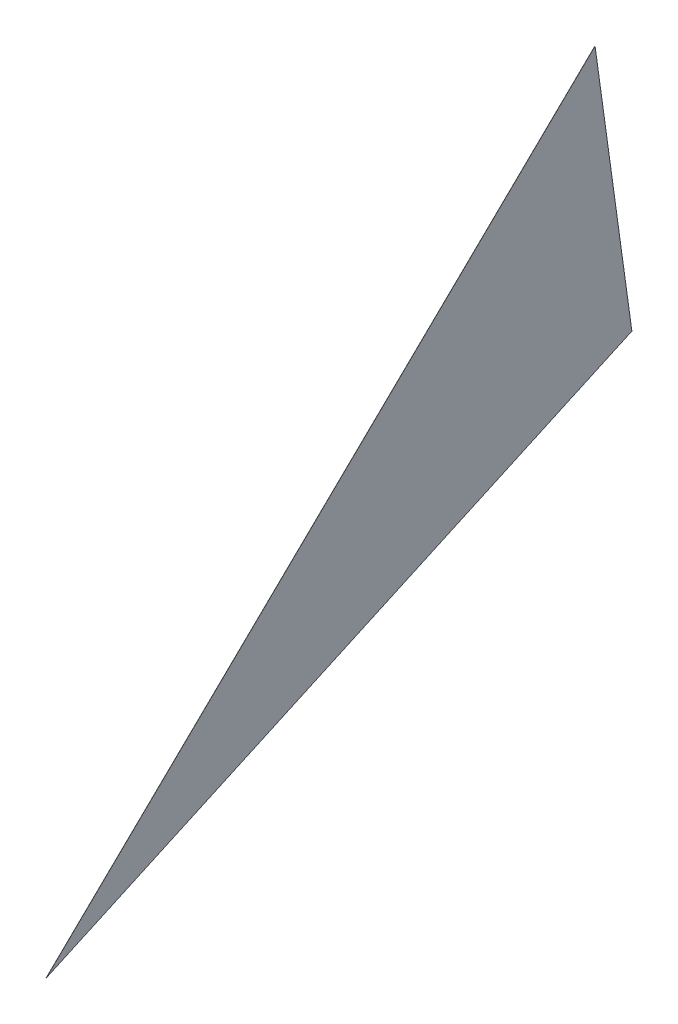
SolidWorks part; units mm, degrees
ref_plane "Front Plane" through (0, 0, 0) normal (0, 0, 1) x (1, 0, 0)
ref_plane "Top Plane" through (0, 0, 0) normal (0, 1, 0) x (1, 0, 0)
ref_plane "Right Plane" through (0, 0, 0) normal (1, 0, 0) x (0, 0, -1)
sketch "Sketch1" plane through (0, 0, 0) normal (1, 0, 0) x (0, 0, -1)
  line L0 (0, 0) -> (115.526, 52.7516)
  line L1 (115.526, 52.7516) -> (108.2649, 105.0823)
  line L2 (108.2649, 105.0823) -> (0, 0)
extrude "Boss-Extrude1" add sketch "Sketch1" along normal blind 0.0254 contours L0 L1 L2
